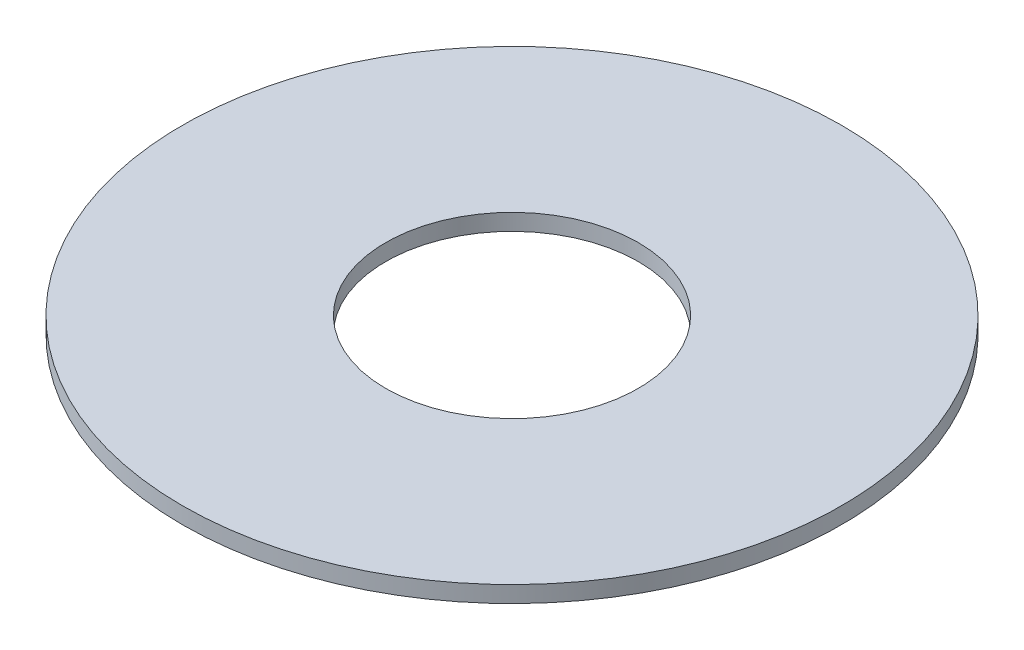
SolidWorks part; units mm, degrees
ref_plane "Front Plane" through (0, 0, 0) normal (0, 0, 1) x (1, 0, 0)
ref_plane "Top Plane" through (0, 0, 0) normal (0, 1, 0) x (1, 0, 0)
ref_plane "Right Plane" through (0, 0, 0) normal (1, 0, 0) x (0, 0, -1)
sketch "Sketch1" plane through (0, 0, 0) normal (0, 1, 0) x (1, 0, 0)
  circle A0 centre (0, 0) radius 30
  circle A1 centre (0, 0) radius 11.5
  dimension "D1" = 23
  dimension "D2" = 60
extrude "Boss-Extrude1" add sketch "Sketch1" along normal blind 1.5
